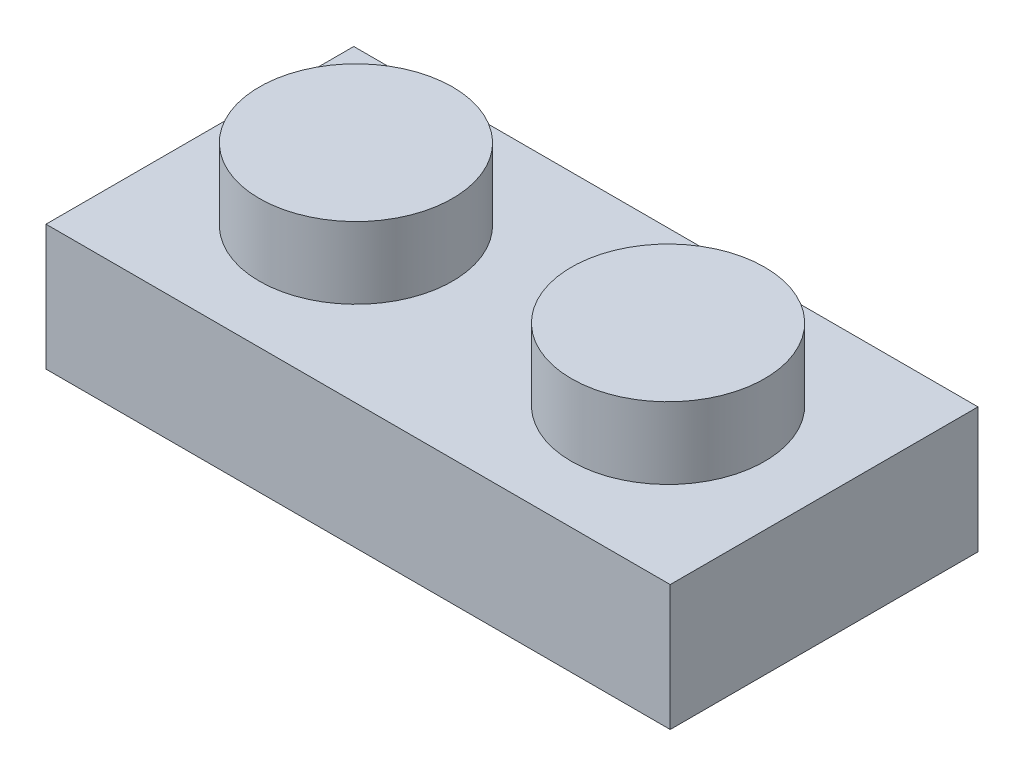
SolidWorks part; units mm, degrees
ref_plane "Front Plane" through (0, 0, 0) normal (0, 0, 1) x (1, 0, 0)
ref_plane "Top Plane" through (0, 0, 0) normal (0, 1, 0) x (1, 0, 0)
ref_plane "Right Plane" through (0, 0, 0) normal (1, 0, 0) x (0, 0, -1)
sketch "Sketch1" plane through (0, 0, 0) normal (0, 1, 0) x (1, 0, 0)
  line L1 (-7.93, 3.91) -> (7.93, 3.91)
  line L2 (-7.93, 3.91) -> (-7.93, -3.91)
  line L3 (-7.93, -3.91) -> (7.93, -3.91)
  line L4 (7.93, 3.91) -> (7.93, -3.91)
  line L5 (-7.93, 3.91) -> (7.93, -3.91) construction
  line L6 (-7.93, -3.91) -> (7.93, 3.91) construction
  point P0 (0, 0)
  dimension "D1" = 7.82
  dimension "D2" = 15.86
extrude "Boss-Extrude1" add sketch "Sketch1" against normal blind 3.19
sketch "Sketch2" plane through (0, 0, 0) normal (0, 1, 0) x (1, 0, 0)
  line L1 (7.93, -3.91) -> (7.93, 3.91) construction
  line L2 (-7.93, -3.91) -> (7.93, -3.91) construction
  line L3 (-7.93, 3.91) -> (-7.93, -3.91) construction
  circle A0 centre (3.965, 0) radius 2.455
  circle A1 centre (-3.965, 0) radius 2.455
  point P8 (0, 0)
  dimension "D1" = 4.91
  dimension "D2" = 4.91
  dimension "D3" = 3.965
  dimension "D4" = 3.91
  dimension "D5" = 3.965
extrude "Boss-Extrude2" add sketch "Sketch2" along normal blind 1.82
shell "Shell1" thickness 1.55
sketch "Sketch3" plane through (0, -1.55, 0) normal (0, -1, 0) x (1, 0, 0)
  circle A0 centre (0, 0) radius 1.485
  circle A1 centre (0, 0) radius 0.68
  dimension "D1" = 2.97
  dimension "D2" = 1.36
extrude "Boss-Extrude3" add sketch "Sketch3" along normal offset from surface (1.44 mm away) 0.2 up to face at (0, -3.19, 0)
